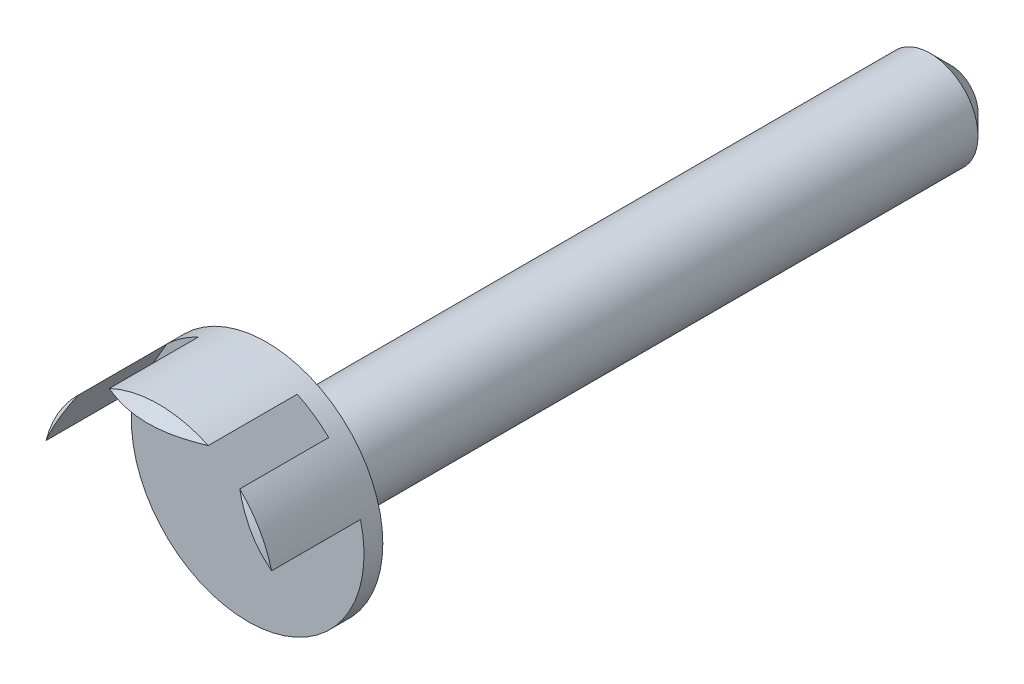
SolidWorks part; units mm, degrees
material "Plain Carbon Steel"
ref_plane "Front" through (0, 0, 0) normal (0, 0, 1) x (1, 0, 0)
ref_plane "Top" through (0, 0, 0) normal (0, 1, 0) x (1, 0, 0)
ref_plane "Right" through (0, 0, 0) normal (1, 0, 0) x (0, 0, -1)
sketch "Sketch1" plane through (0, 0, 0) normal (0, 0, 1) x (1, 0, 0)
  circle A0 centre (0, 0) radius 1.778
  dimension "D1" = 3.556
extrude "Extrude1" add sketch "Sketch1" along normal blind 25.4
sketch "Sketch3" plane through (0, 0, 25.4) normal (0, 0, 1) x (1, 0, 0)
  circle A0 centre (0, 0.4916) radius 4.318
  dimension "D1" = 8.636
extrude "Extrude3" add sketch "Sketch3" along normal blind 4.7625
chamfer "Chamfer1" distance 0.762 angle 45 2 edges at (1.778, 0, 0) (4.318, 0.4916, 30.1625)
sketch "Sketch4" plane through (0, 0, 30.1625) normal (0, 0, 1) x (1, 0, 0)
  line L0 (8.7312, 0) -> (-8.7312, 0) construction
  line L1 (5.08, 0) -> (2.54, 4.3994)
  line L2 (2.54, 4.3994) -> (-2.54, 4.3994)
  line L3 (-2.54, 4.3994) -> (-5.08, 0)
  line L4 (-5.08, 0) -> (-2.54, -4.3994)
  line L5 (-2.54, -4.3994) -> (2.54, -4.3994)
  line L6 (2.54, -4.3994) -> (5.08, 0)
  circle A0 centre (0, 0) radius 4.3994 construction
  dimension "D1" = 5.08
extrude "Cut-Extrude1" cut sketch "Sketch4" against normal blind 4.064
